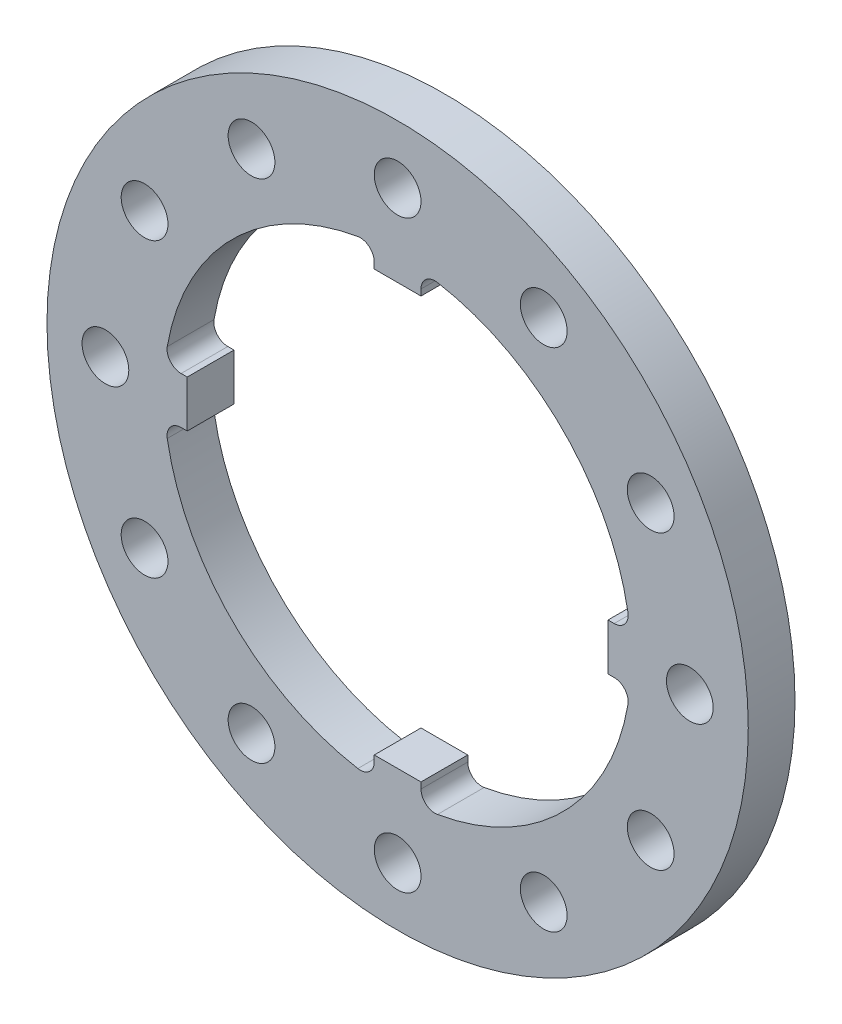
SolidWorks part; units mm, degrees
ref_plane "Front Plane" through (0, 0, 0) normal (0, 0, 1) x (1, 0, 0)
ref_plane "Top Plane" through (0, 0, 0) normal (0, 1, 0) x (1, 0, 0)
ref_plane "Right Plane" through (0, 0, 0) normal (1, 0, 0) x (0, 0, -1)
sketch "Sketch1" plane through (0, 0, 0) normal (0, 0, 1) x (1, 0, 0)
  line L0 (0, 0) -> (0, -50000) construction
  line L1 (0, 0) -> (-50000, 0) construction
  line L2 (45, 5) -> (46.3141, 5)
  line L3 (45, -5) -> (46.3141, -5)
  line L4 (45, 5) -> (45, -5)
  line L5 (5, -45) -> (5, -46.3141)
  line L6 (5, -45) -> (-5, -45)
  line L7 (-5, -45) -> (-5, -46.3141)
  line L8 (-45, -5) -> (-46.3141, -5)
  line L9 (-45, -5) -> (-45, 5)
  line L10 (-45, 5) -> (-46.3141, 5)
  line L11 (-5, 45) -> (-5, 46.3141)
  line L12 (-5, 45) -> (5, 45)
  line L13 (5, 45) -> (5, 46.3141)
  circle A0 centre (0, 0) radius 75
  arc A1 (49.2704, 8.5106) -> (8.5106, 49.2704) centre (0, 0) ccw
  arc A2 (46.3141, 5) -> (49.2704, 8.5106) centre (46.3141, 8) ccw
  arc A3 (46.3141, -5) -> (49.2704, -8.5106) centre (46.3141, -8) cw
  arc A4 (5, -46.3141) -> (8.5106, -49.2704) centre (8, -46.3141) ccw
  arc A5 (-5, -46.3141) -> (-8.5106, -49.2704) centre (-8, -46.3141) cw
  arc A6 (-46.3141, -5) -> (-49.2704, -8.5106) centre (-46.3141, -8) ccw
  arc A7 (-46.3141, 5) -> (-49.2704, 8.5106) centre (-46.3141, 8) cw
  arc A8 (-5, 46.3141) -> (-8.5106, 49.2704) centre (-8, 46.3141) ccw
  arc A9 (5, 46.3141) -> (8.5106, 49.2704) centre (8, 46.3141) cw
  arc A10 (-8.5106, 49.2704) -> (-49.2704, 8.5106) centre (0, 0) ccw
  arc A11 (-49.2704, -8.5106) -> (-8.5106, -49.2704) centre (0, 0) ccw
  arc A12 (8.5106, -49.2704) -> (49.2704, -8.5106) centre (0, 0) ccw
  circle A13 centre (0, 0) radius 62.5 construction
  circle A14 centre (62.5, 0) radius 5
  circle A15 centre (54.1266, -31.25) radius 5
  circle A16 centre (31.25, -54.1266) radius 5
  circle A17 centre (0, -62.5) radius 5
  circle A18 centre (-31.25, -54.1266) radius 5
  circle A19 centre (-54.1266, -31.25) radius 5
  circle A20 centre (-62.5, 0) radius 5
  circle A21 centre (-54.1266, 31.25) radius 5
  circle A22 centre (-31.25, 54.1266) radius 5
  circle A23 centre (0, 62.5) radius 5
  circle A24 centre (31.25, 54.1266) radius 5
  circle A25 centre (54.1266, 31.25) radius 5
  point P10 (45, 0)
  point P12 (45.6571, -5)
  point P44 (0, 0)
  point P45 (0, 0)
  point P69 (0, 0)
  dimension "D1" = 150
  dimension "D2" = 100
  dimension "D5" = 3
  dimension "D6" = 47
  dimension "D7" = 4
  dimension "D8" = 125
  dimension "D9" = 10
  dimension "D3" = 10
  dimension "D4" = 45
  dimension "D10" = 12
extrude "Boss-Extrude1" add sketch "Sketch1" along normal mid plane 10
